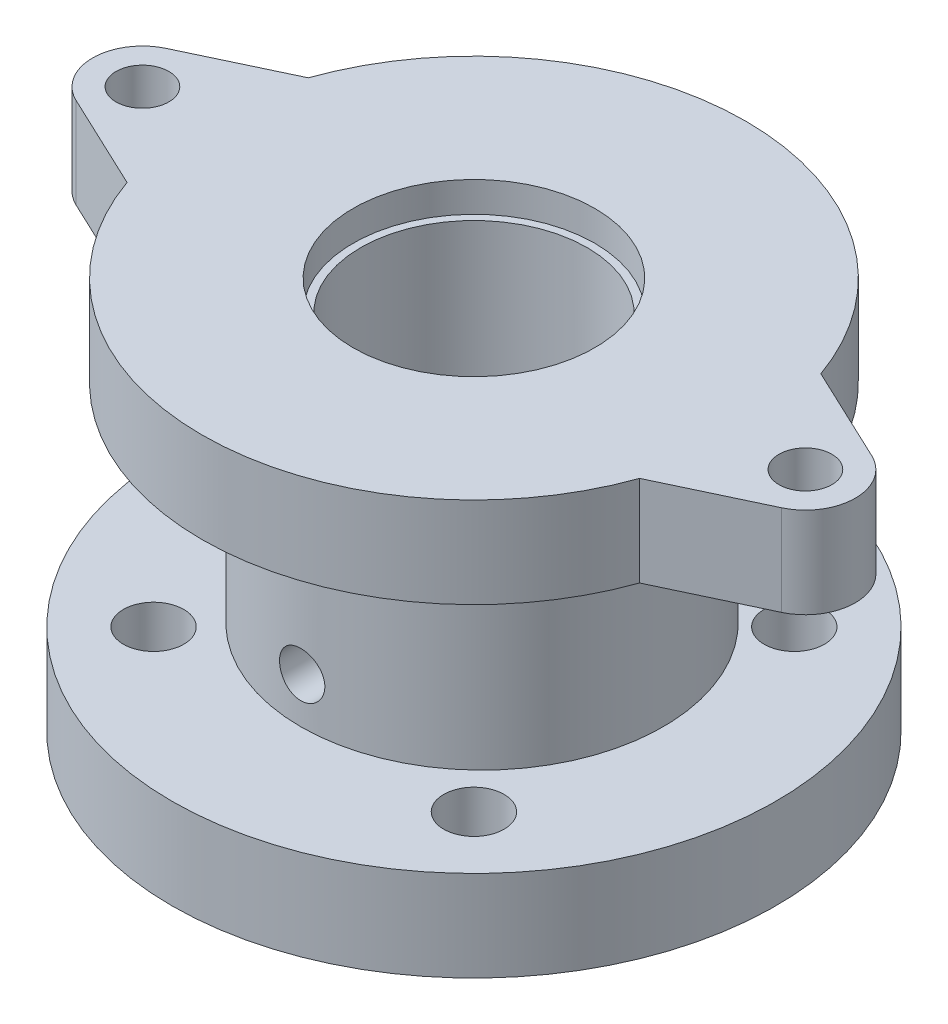
SolidWorks part; units mm, degrees
material "PLA Generic"
ref_plane "Front Plane" through (0, 0, 0) normal (0, 0, 1) x (1, 0, 0)
ref_plane "Top Plane" through (0, 0, 0) normal (0, 1, 0) x (1, 0, 0)
ref_plane "Right Plane" through (0, 0, 0) normal (1, 0, 0) x (0, 0, -1)
sketch "Sketch1" plane through (0, 0, 0) normal (0, 1, 0) x (1, 0, 0)
  circle A0 centre (0, 0) radius 7.5
  circle A1 centre (0, 0) radius 20
  dimension "D1" = 40
  dimension "D2" = 15
extrude "Boss-Extrude1" add sketch "Sketch1" along normal blind 6
sketch "Sketch2" plane through (0, 6, 0) normal (0, 1, 0) x (1, 0, 0)
  circle A0 centre (0, 0) radius 7.5
  circle A1 centre (0, 0.5354) radius 12
  dimension "D1" = 24
extrude "Boss-Extrude2" add sketch "Sketch2" along normal blind 14
sketch "Sketch3" plane through (0, 0, 0) normal (0, 0, 1) x (1, 0, 0)
  circle A0 centre (0, 9) radius 1.5
  dimension "D1" = 9
  dimension "D2" = 3
extrude "Cut-Extrude1" cut sketch "Sketch3" against normal through all both and the other way through all
sketch "Sketch4" plane through (0, 20, 0) normal (0, 1, 0) x (1, 0, 0)
  circle A0 centre (0, 0) radius 18
  circle A1 centre (0, 0) radius 7.5
  dimension "D1" = 36
extrude "Boss-Extrude3" add sketch "Sketch4" along normal blind 6
sketch "Sketch5" plane through (0, 26, 0) normal (0, 1, 0) x (1, 0, 0)
  line L0 (-21.95, 0) -> (21.95, 0) construction
  line L1 (-23.3588, 2.9842) -> (-16.9706, 6)
  line L2 (-23.3588, -2.9842) -> (-16.9706, -6)
  line L3 (23.3588, 2.9842) -> (16.9706, 6)
  line L4 (23.3588, -2.9842) -> (16.9706, -6)
  line L5 (-25.25, 0) -> (25.25, 0) construction
  circle A0 centre (-21.95, 0) radius 1.75
  circle A1 centre (21.95, 0) radius 1.75
  arc A2 (-23.3588, 2.9842) -> (-23.3588, -2.9842) centre (-21.95, 0) ccw
  arc A3 (23.3588, -2.9842) -> (23.3588, 2.9842) centre (21.95, 0) ccw
  arc A4 (-16.9706, 6) -> (-16.9706, -6) centre (0, 0) ccw
  arc A5 (16.9706, -6) -> (16.9706, 6) centre (0, 0) ccw
  circle A6 centre (0, 0) radius 18 construction
  point P3 (0, 0)
  point P14 (18, 0)
  point P15 (0, 0)
  point P16 (-18, 0)
  dimension "D2" = 3.5
  dimension "D3" = 3.5
  dimension "D1" = 43.9
  dimension "D4" = 12
  dimension "D5" = 50.5
extrude "Boss-Extrude4" add sketch "Sketch5" against normal up to surface (6 mm away) up to face at (0, 20, 11.4646)
sketch "Sketch6" plane through (0, 0, 0) normal (0, -1, 0) x (1, 0, 0)
  line L0 (0, 0) -> (-18.2577, 0) construction
  line L1 (0, 0) -> (-10.6066, 10.6066) construction
  circle A0 centre (-10.6066, 10.6066) radius 2
  circle A1 centre (10.6066, 10.6066) radius 2
  circle A2 centre (10.6066, -10.6066) radius 2
  circle A3 centre (-10.6066, -10.6066) radius 2
  point P14 (0, 0)
  dimension "D2" = 15
  dimension "D3" = 4
  dimension "D1" = 45
  dimension "D4" = 4
extrude "Cut-Extrude2" cut sketch "Sketch6" against normal up to surface (6 mm away) and the other way through all up to face at (0, 6, 20)
sketch "Sketch7" plane through (0, 26, 0) normal (0, 1, 0) x (1, 0, 0)
  circle A0 centre (0, 0) radius 8
  dimension "D1" = 16
extrude "Cut-Extrude3" cut sketch "Sketch7" against normal blind 2
ref_plane "Plane3" through (0, -192.3, 0) normal (0, -1, 0) x (-1, 0, 0)
sketch "Sketch10" plane through (0, -192.3, 0) normal (0, -1, 0) x (-1, 0, 0)
  point P0 (0, 0)
